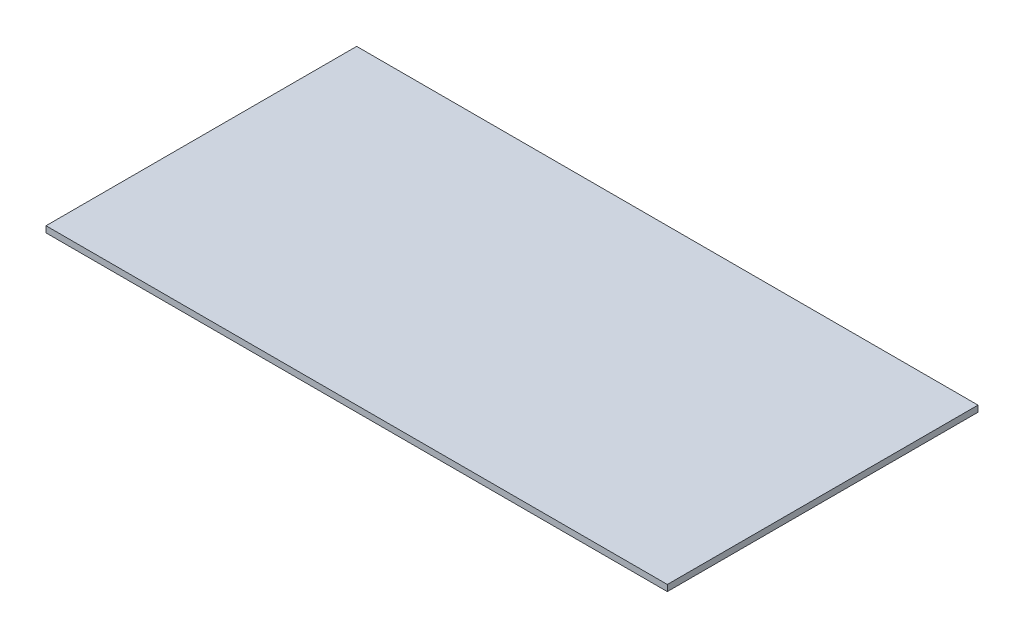
SolidWorks part; units mm, degrees
ref_plane "Front Plane" through (0, 0, 0) normal (0, 0, 1) x (1, 0, 0)
ref_plane "Top Plane" through (0, 0, 0) normal (0, 1, 0) x (1, 0, 0)
ref_plane "Right Plane" through (0, 0, 0) normal (1, 0, 0) x (0, 0, -1)
sketch "Sketch1" plane through (0, 0, 0) normal (0, 1, 0) x (1, 0, 0)
  line L1 (-158.75, -79.375) -> (158.75, -79.375)
  line L2 (-158.75, -79.375) -> (-158.75, 79.375)
  line L3 (-158.75, 79.375) -> (158.75, 79.375)
  line L4 (158.75, -79.375) -> (158.75, 79.375)
  line L5 (-158.75, -79.375) -> (158.75, 79.375) construction
  line L6 (-158.75, 79.375) -> (158.75, -79.375) construction
  point P0 (0, 0)
  dimension "D1" = 158.75
  dimension "D2" = 317.5
extrude "Boss-Extrude1" add sketch "Sketch1" along normal blind 3.175
